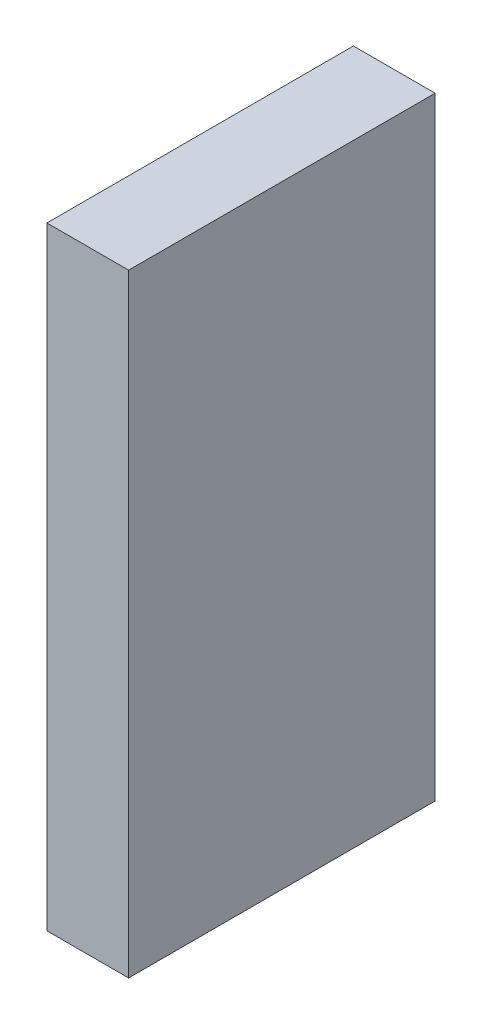
SolidWorks part; units mm, degrees
ref_plane "Front Plane" through (0, 0, 0) normal (0, 0, 1) x (1, 0, 0)
ref_plane "Top Plane" through (0, 0, 0) normal (0, 1, 0) x (1, 0, 0)
ref_plane "Right Plane" through (0, 0, 0) normal (1, 0, 0) x (0, 0, -1)
other "Configuration Table"
sketch "Sketch1" plane through (0, 0, 0) normal (0, 0, 1) x (1, 0, 0)
  line L1 (346, 700) -> (354, 700)
  line L2 (346, 700) -> (346, 760)
  line L3 (346, 760) -> (354, 760)
  line L4 (354, 700) -> (354, 760)
extrude "PACK_flap_parmagi_2_1" add sketch "Sketch1" against normal blind 30 from offset 185 separate body
